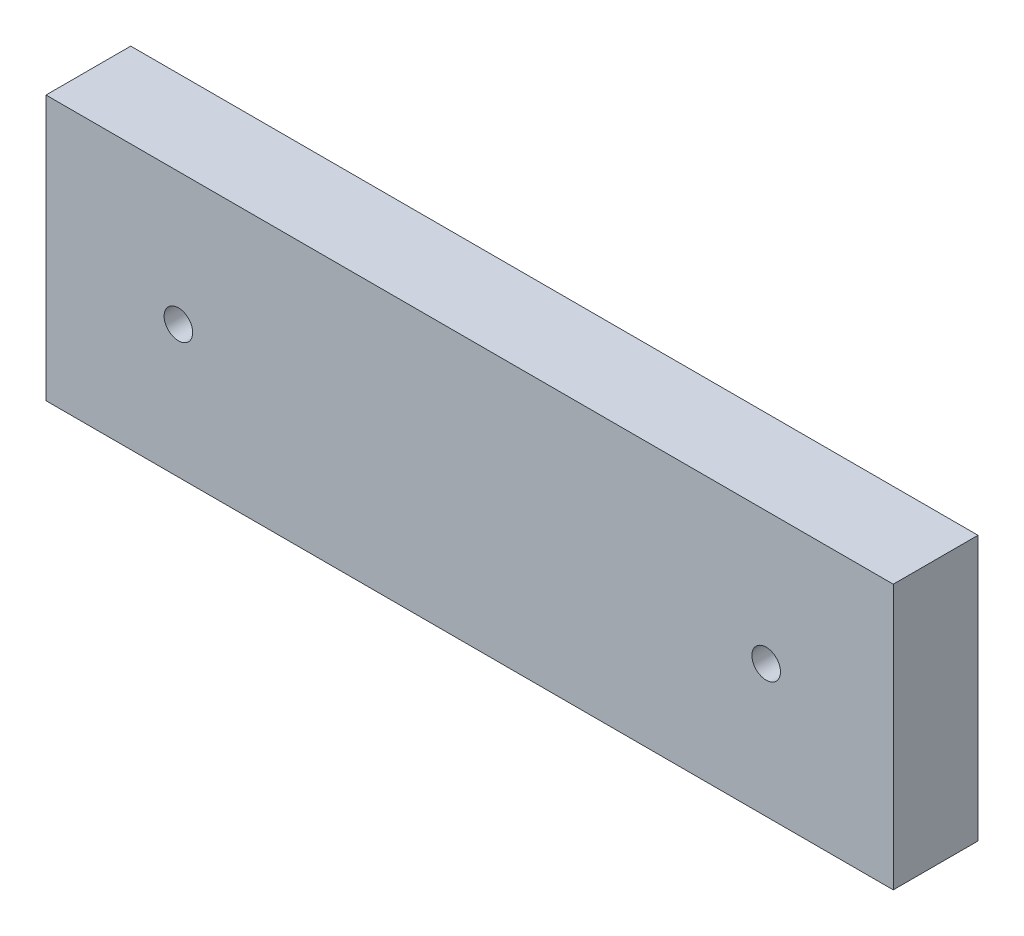
SolidWorks part; units mm, degrees
ref_plane "前视基准面" through (0, 0, 0) normal (0, 0, 1) x (1, 0, 0)
ref_plane "上视基准面" through (0, 0, 0) normal (0, 1, 0) x (1, 0, 0)
ref_plane "右视基准面" through (0, 0, 0) normal (1, 0, 0) x (0, 0, -1)
sketch "草图1" plane through (0, 0, 0) normal (0, 0, 1) x (1, 0, 0)
  line L1 (0, 0) -> (80, 0)
  line L2 (0, 0) -> (0, -25)
  line L3 (0, -25) -> (80, -25)
  line L4 (80, 0) -> (80, -25)
  dimension "D1" = 80
  dimension "D2" = 25
extrude "凸台-拉伸1" add sketch "草图1" along normal blind 8
sketch "草图2" plane through (0, 0, 0) normal (0, 0, -1) x (-1, 0, 0)
  line L0 (-68, -12.5) -> (-12.5, -12.5) construction
  line L1 (-68, -10.85) -> (-12.5, -10.85)
  line L2 (-68, -14.15) -> (-12.5, -14.15)
  arc A0 (-68, -10.85) -> (-68, -14.15) centre (-68, -12.5) ccw
  arc A1 (-12.5, -14.15) -> (-12.5, -10.85) centre (-12.5, -12.5) ccw
  point P2 (-40.25, -12.5)
  dimension "D1" = 1.65
  dimension "D2" = 12.5
  dimension "D4" = 55.5
  dimension "D5" = 12
extrude "凸台-拉伸2" add sketch "草图2" along normal blind 1.7
sketch "草图3" plane through (0, 0, -1.7) normal (0, 0, -1) x (-1, 0, 0)
  circle A0 centre (-68, -12.5) radius 1.35
  circle A1 centre (-12.5, -12.5) radius 1.35
  arc A2 (-68, -10.85) -> (-68, -14.15) centre (-68, -12.5) ccw construction
  arc A3 (-12.5, -14.15) -> (-12.5, -10.85) centre (-12.5, -12.5) ccw construction
  dimension "D1" = 2.7
sketch "草图5" plane through (0, -14.15, 0) normal (0, -1, 0) x (1, 0, 0)
  line L0 (68, 0) -> (12.5, 0) construction
  line L1 (39.1, 0) -> (41.3, 0)
  line L2 (39.1, 0) -> (39.1, -1.7)
  line L3 (39.1, -1.7) -> (41.3, -1.7)
  line L4 (41.3, 0) -> (41.3, -1.7)
  line L6 (68, -1.7) -> (12.5, -1.7) construction
  dimension "D1" = 26.6
  dimension "D2" = 2.2
extrude "切除-拉伸1" cut sketch "草图5" against normal blind 7
extrude "切除-拉伸2" cut sketch "草图3" against normal through all
